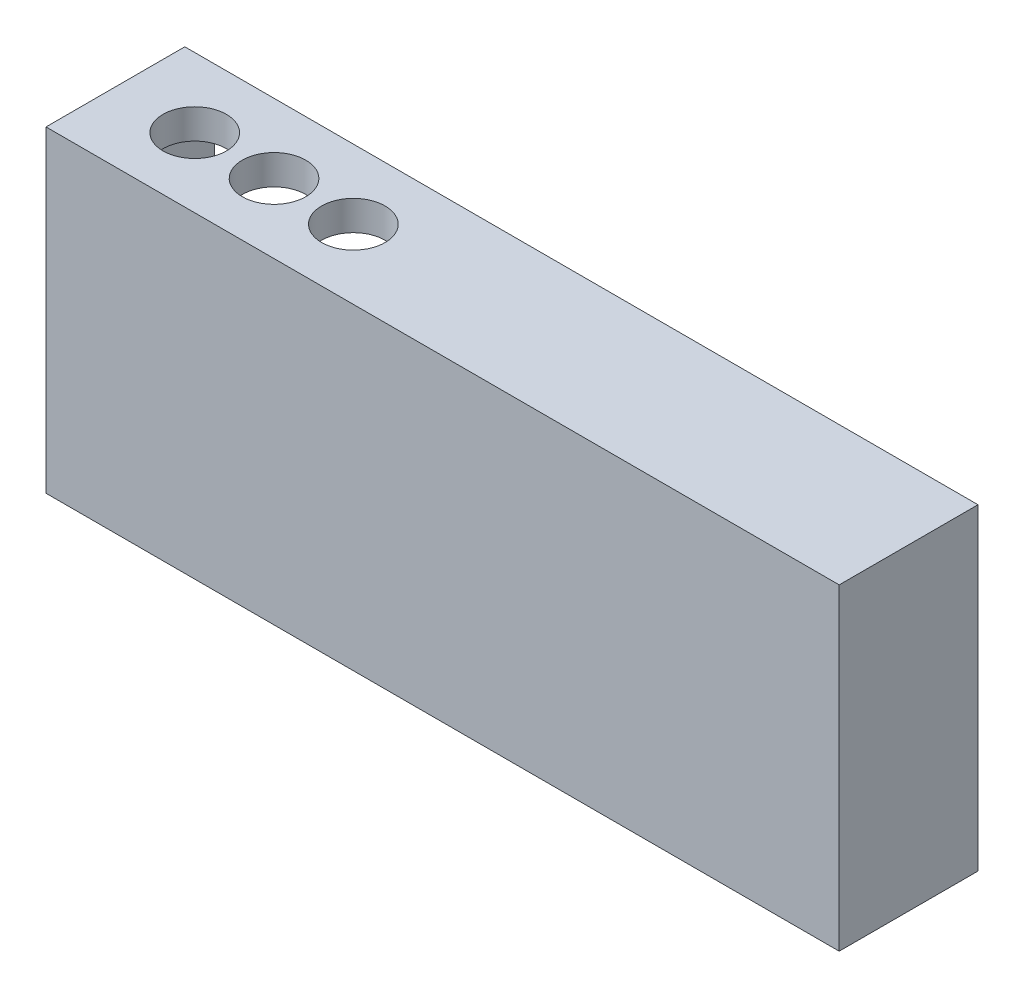
SolidWorks part; units mm, degrees
ref_plane "Alzado" through (0, 0, 0) normal (0, 0, 1) x (1, 0, 0)
ref_plane "Planta" through (0, 0, 0) normal (0, 1, 0) x (1, 0, 0)
ref_plane "Vista lateral" through (0, 0, 0) normal (1, 0, 0) x (0, 0, -1)
sketch "Croquis1" plane through (0, 0, 0) normal (0, 0, 1) x (1, 0, 0)
  line L1 (-100, -40) -> (100, -40)
  line L2 (-100, -40) -> (-100, 40)
  line L3 (-100, 40) -> (100, 40)
  line L4 (100, -40) -> (100, 40)
  line L5 (-100, -40) -> (100, 40) construction
  line L6 (-100, 40) -> (100, -40) construction
  point P0 (0, 0)
  dimension "D1" = 200
  dimension "D2" = 80
extrude "Saliente-Extruir1" add sketch "Croquis1" along normal blind 35
sketch "Croquis2" plane through (0, 0, 0) normal (0, 0, -1) x (-1, 0, 0)
  line L1 (-92.5, -32.5) -> (92.5, -32.5)
  line L2 (-92.5, -32.5) -> (-92.5, 32.5)
  line L3 (-92.5, 32.5) -> (92.5, 32.5)
  line L4 (92.5, -32.5) -> (92.5, 32.5)
  line L5 (-92.5, -32.5) -> (92.5, 32.5) construction
  line L6 (-92.5, 32.5) -> (92.5, -32.5) construction
  point P1 (0, 0)
  dimension "D1" = 185
  dimension "D2" = 65
extrude "Cortar-Extruir1" cut sketch "Croquis2" against normal blind 27.5
sketch "Croquis3" plane through (0, 40, 0) normal (0, 1, 0) x (1, 0, 0)
  line L0 (-100, -17.5) -> (100, -17.5) construction
  line L1 (-100, -35) -> (-100, 0) construction
  line L2 (100, -35) -> (100, 0) construction
  circle A0 centre (-80, -17.5) radius 8
  circle A1 centre (-60, -17.5) radius 8
  circle A2 centre (-40, -17.5) radius 8
  dimension "D1" = 16
  dimension "D2" = 16
  dimension "D3" = 16
  dimension "D4" = 20
  dimension "D5" = 20
  dimension "D6" = 20
extrude "Cortar-Extruir2" cut sketch "Croquis3" against normal blind 7.5
sketch "Croquis4" plane through (0, -40, 0) normal (0, -1, 0) x (1, 0, 0)
  line L0 (100, 17.5) -> (-100, 17.5) construction
  line L1 (100, 35) -> (100, 0) construction
  line L2 (-100, 35) -> (-100, 0) construction
  circle A0 centre (80, 17.5) radius 5.4
  dimension "D1" = 10.8
  dimension "D2" = 20
extrude "Cortar-Extruir3" cut sketch "Croquis4" against normal blind 7.5
sketch "Croquis5" plane through (0, 0, 0) normal (0, 0, -1) x (-1, 0, 0)
  line L0 (100, 40) -> (100, -40) construction
  line L1 (100, -40) -> (-100, -40) construction
  circle A0 centre (96.25, -36.25) radius 2.5092
  circle A1 centre (-96.25, -36.25) radius 2.5092
  circle A2 centre (-96.25, 36.25) radius 2.5092
  circle A3 centre (96.25, 36.25) radius 2.5092
  dimension "D1" = 5.0184
  dimension "D2" = 3.75
  dimension "D3" = 3.75
  dimension "D4" = 2
  dimension "D5" = 2
extrude "Cortar-Extruir4" cut sketch "Croquis5" against normal blind 2 contours A0 | A3 | A2 | A1
